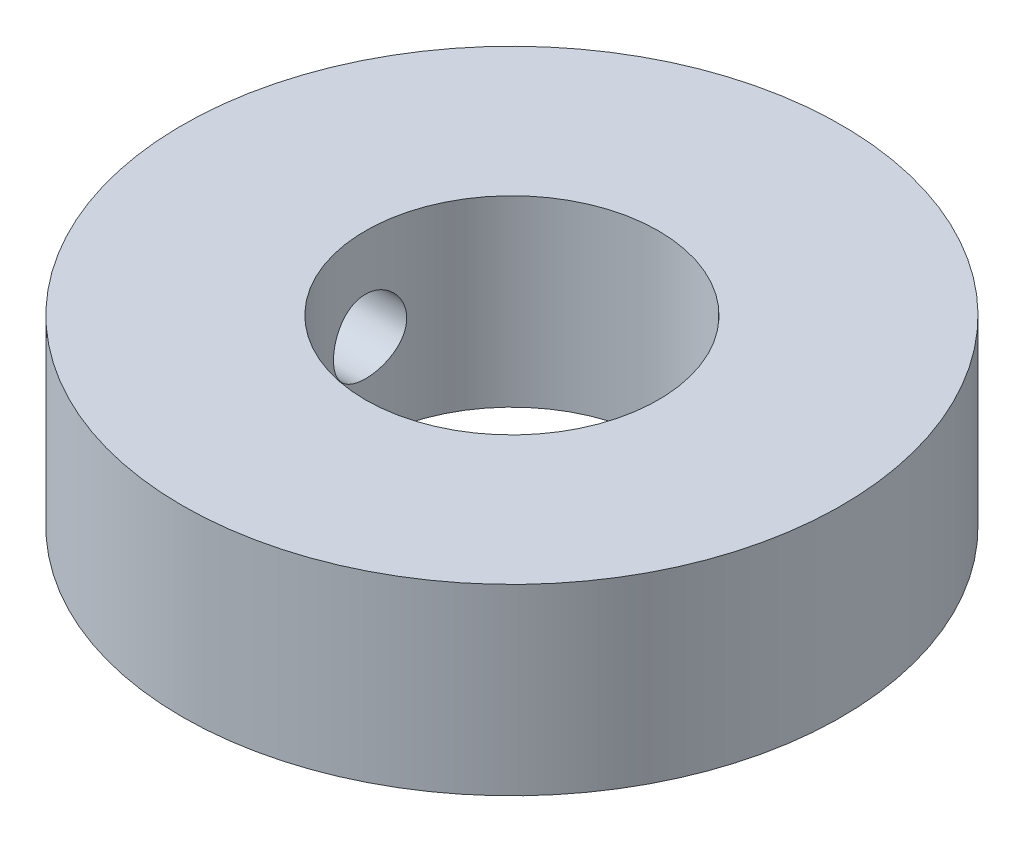
SolidWorks part; units mm, degrees
material "1060 合金"
ref_plane "前视基准面" through (0, 0, 0) normal (0, 0, 1) x (1, 0, 0)
ref_plane "上视基准面" through (0, 0, 0) normal (0, 1, 0) x (1, 0, 0)
ref_plane "右视基准面" through (0, 0, 0) normal (1, 0, 0) x (0, 0, -1)
sketch "草图1" plane through (0, 0, 0) normal (0, 1, 0) x (1, 0, 0)
  circle A0 centre (0, 0) radius 4
  circle A1 centre (0, 0) radius 9
  dimension "D1" = 8
  dimension "D2" = 18
extrude "凸台-拉伸1" add sketch "草图1" along normal blind 5
sketch "草图2" plane through (0, 0, 0) normal (1, 0, 0) x (0, 0, -1)
  line L0 (0, 0) -> (0, 13.9847) construction
  circle A0 centre (0, 2.5) radius 1
  dimension "D2" = 2
  dimension "D1" = 2.5
extrude "切除-拉伸1" cut sketch "草图2" against normal blind 15
